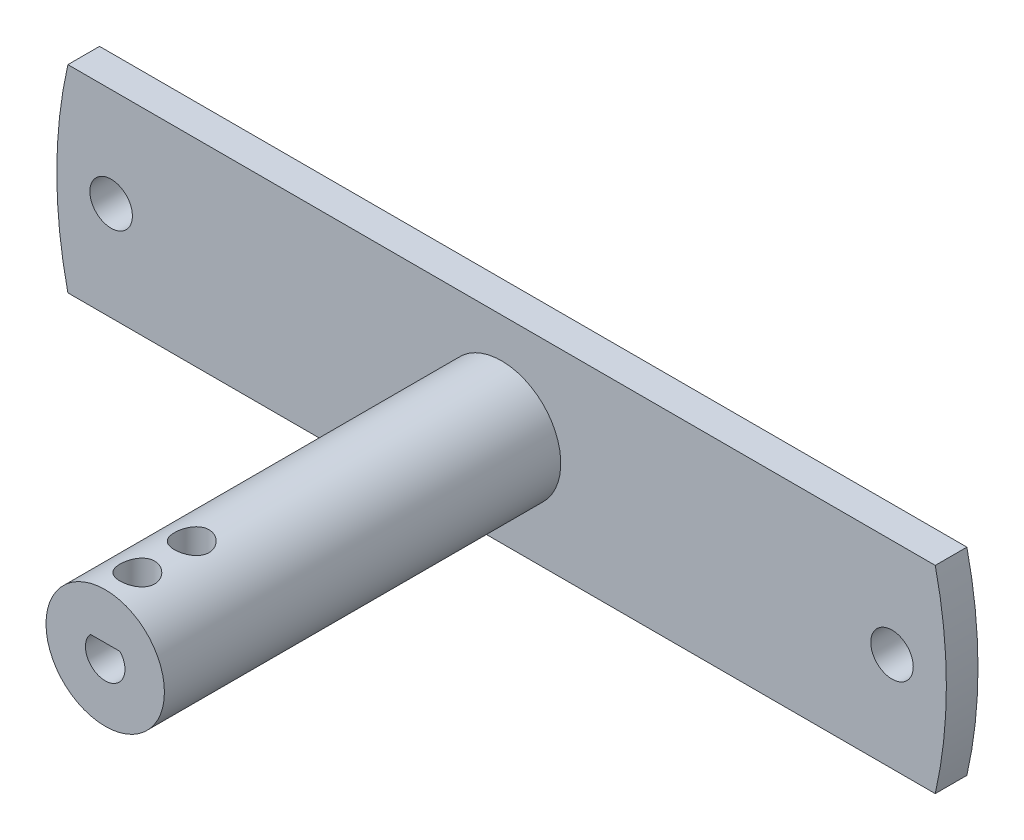
SolidWorks part; units mm, degrees
ref_plane "Alzado" through (0, 0, 0) normal (0, 0, 1) x (1, 0, 0)
ref_plane "Planta" through (0, 0, 0) normal (0, 1, 0) x (1, 0, 0)
ref_plane "Vista lateral" through (0, 0, 0) normal (1, 0, 0) x (0, 0, -1)
sketch "Croquis1" plane through (0, 0, 0) normal (0, 0, 1) x (1, 0, 0)
  line L0 (0, 0) -> (0, 1.3229) construction
  line L7 (-1.5, 1.3229) -> (1.5, 1.3229)
  circle A0 centre (0, 0) radius 5.99
  arc A1 (-1.5, 1.3229) -> (1.5, 1.3229) centre (0, 0) ccw
  point P14 (0, 1.3229)
  dimension "D2" = 4
  dimension "D1" = 11.98
  dimension "D4" = 2
  dimension "D3" = 3
extrude "Saliente-Extruir1" add sketch "Croquis1" along normal blind 43.3
sketch "Croquis2" plane through (0, 1.3229, 0) normal (0, 1, 0) x (1, 0, 0)
  line L0 (0, -43.3) -> (0, -40.05) construction
  line L2 (0, -40.05) -> (0, -38.3) construction
  line L3 (0, -38.3) -> (0, -36.3) construction
  line L4 (0, -36.3) -> (0, -34.55) construction
  line L5 (0, -34.55) -> (0, -31.3) construction
  line L6 (-5.99, -43.3) -> (5.99, -43.3) construction
  circle A0 centre (0, -40.05) radius 1.75
  circle A1 centre (0, -34.55) radius 1.75
  dimension "D1" = 3.5
  dimension "D2" = 12
  dimension "D3" = 2
extrude "Cortar-Extruir1" cut sketch "Croquis2" along normal blind 7.5
sketch "Croquis3" plane through (0, 0, 0) normal (0, 0, -1) x (-1, 0, 0)
  circle A0 centre (0, 0) radius 45
  dimension "D1" = 90
extrude "Saliente-Extruir2" add sketch "Croquis3" against normal blind 3.2
sketch "Croquis5" plane through (0, 0, 0) normal (0, 0, -1) x (-1, 0, 0)
  line L0 (0, 0) -> (0, 7.5) construction
  line L1 (0, 7.5) -> (-7.5, 7.5) construction
  line L2 (0, 0) -> (-34, 0) construction
  line L3 (-34, 0) -> (-45, 0) construction
  line L4 (0, 7.5) -> (0, 10) construction
  line L5 (0, 10) -> (-75, 10)
  line L6 (-75, 10) -> (-75, 50)
  line L7 (-75, 50) -> (75, 50)
  line L8 (75, 50) -> (75, 10)
  line L9 (75, 10) -> (0, 10)
  line L10 (75, -50) -> (75, -10)
  line L11 (-75, -50) -> (75, -50)
  line L12 (-75, -10) -> (-75, -50)
  line L13 (0, -10) -> (-75, -10)
  line L14 (75, -10) -> (0, -10)
  circle A4 centre (0, 0) radius 45 construction
  circle A5 centre (-39.5, 0) radius 2.15
  circle A6 centre (39.5, 0) radius 2.15
  point P14 (0.2713, -0.2713)
  dimension "D3" = 45
  dimension "D5" = 4.3
  dimension "D1" = 7.5
  dimension "D2" = 7.5
  dimension "D4" = 34
  dimension "D6" = 10
  dimension "D7" = 40
  dimension "D8" = 150
extrude "Cortar-Extruir2" cut sketch "Croquis5" against normal blind 5 and the other way through all
